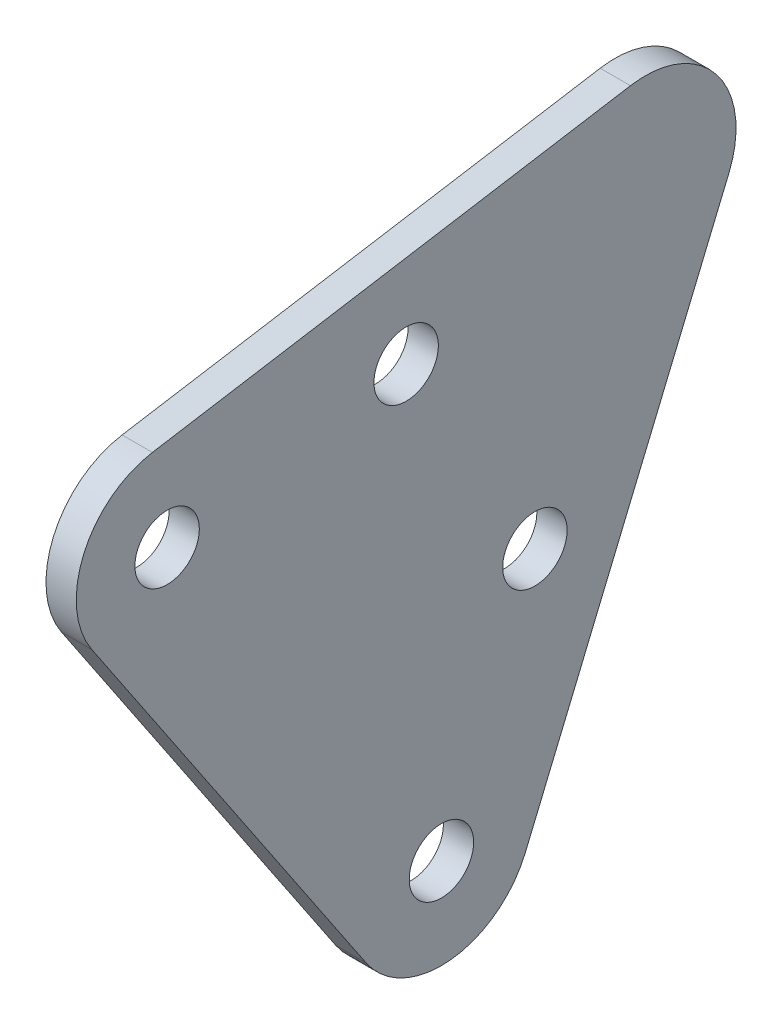
SolidWorks part; units mm, degrees
ref_plane "Front Plane" through (0, 0, 0) normal (0, 0, 1) x (1, 0, 0)
ref_plane "Top Plane" through (0, 0, 0) normal (0, 1, 0) x (1, 0, 0)
ref_plane "Right Plane" through (0, 0, 0) normal (1, 0, 0) x (0, 0, -1)
sketch "Sketch2" plane through (0, 0, 0) normal (1, 0, 0) x (0, 0, -1)
  line L0 (-1159.9868, 353.698) -> (-1134.923, 357.8172) construction
  line L1 (-1166.3499, 338.9894) -> (-1137.588, 296.1543) construction
  line L2 (-1120.8932, 297.7881) -> (-1111.0907, 321.2204) construction
  line L3 (-1092.8913, 364.725) -> (-1111.0907, 321.2204) construction
  line L4 (-1134.923, 357.8172) -> (-1092.8913, 364.725) construction
  line L5 (-1159.9868, 353.698) -> (-1134.923, 357.8172)
  line L6 (-1166.3499, 338.9894) -> (-1137.588, 296.1543)
  line L7 (-1120.8932, 297.7881) -> (-1111.0907, 321.2204)
  line L8 (-1092.8913, 364.725) -> (-1111.0907, 321.2204)
  line L9 (-1134.923, 357.8172) -> (-1092.8913, 364.725)
  circle A0 centre (-1158.4421, 344.2991) radius 9.525 construction
  circle A1 centre (-1129.6803, 301.4641) radius 9.525 construction
  arc A2 (-1159.9868, 353.698) -> (-1166.3499, 338.9894) centre (-1158.4421, 344.2991) ccw
  arc A3 (-1137.588, 296.1543) -> (-1120.8932, 297.7881) centre (-1129.6803, 301.4641) ccw
extrude "Boss-Extrude1" add sketch "Sketch2" along normal up to vertex (96.0438 mm away) from vertex at 92.8688
fillet "Fillet1" radius 9.525 1 edges at (94.4563, 364.725, 1092.8913)
hole_wizard "1/4 Clearance Hole1" positions "Sketch3" profile "Sketch4" hole size "1/4" standard "ANSI Inch" end condition through all
sketch "Sketch3" plane through (96.0438, 0, 0) normal (1, 0, 0) x (0, 0, -1)
  point P0 (-1133.3783, 348.4183)
  point P3 (-1158.4421, 344.2991)
  point P6 (-1129.6803, 301.4641)
  point P9 (-1119.8778, 324.8963)
sketch "Sketch4" plane through (96.0438, 348.4183, 1133.3783) normal (0, 1, 0) x (0, 0, -1)
  line L0 (0, 0) -> (0, 3.175)
  line L1 (0, 3.175) -> (3.3782, 3.175)
  line L2 (3.3782, 3.175) -> (3.3782, 0)
  line L5 (3.3782, 0) -> (0, 0)
  line L11 (0, -6.35) -> (0, 107.95) construction
  dimension "Thru Hole Dia." = 6.7564
  dimension "Thru Hole Depth" = 3.175
